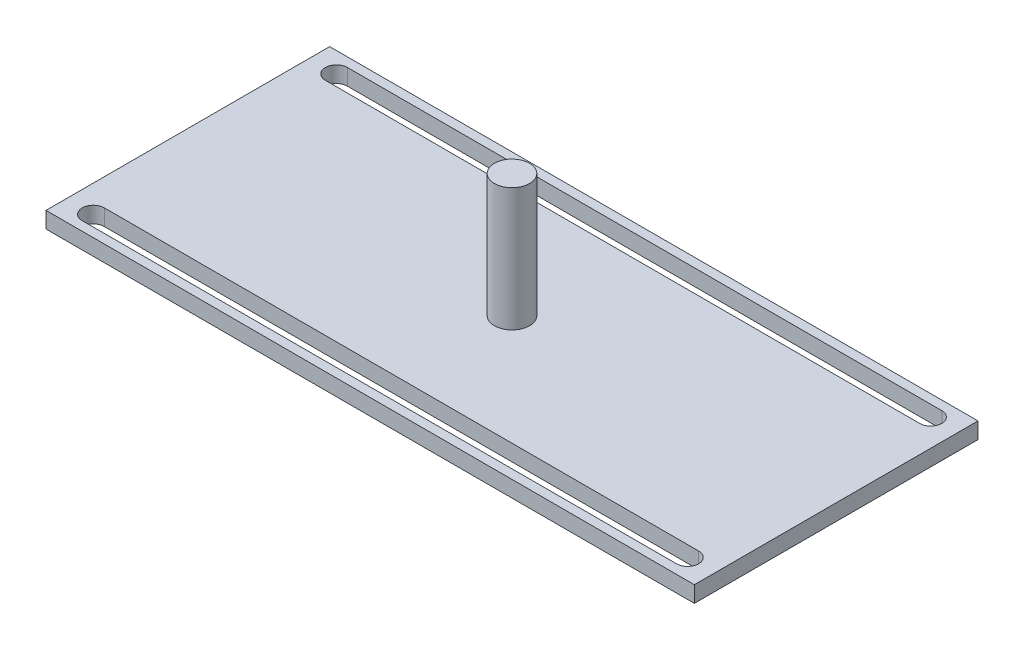
SolidWorks part; units mm, degrees
ref_plane "前视基准面" through (0, 0, 0) normal (0, 0, 1) x (1, 0, 0)
ref_plane "上视基准面" through (0, 0, 0) normal (0, 1, 0) x (1, 0, 0)
ref_plane "右视基准面" through (0, 0, 0) normal (1, 0, 0) x (0, 0, -1)
other "Configuration Table"
sketch "草图2" plane through (0, 0, 0) normal (0, 1, 0) x (1, 0, 0)
  line L1 (-205.4764, 85.5388) -> (34.5236, 85.5388)
  line L2 (-205.4764, 85.5388) -> (-205.4764, -19.4612)
  line L3 (-205.4764, -19.4612) -> (34.5236, -19.4612)
  line L4 (34.5236, 85.5388) -> (34.5236, -19.4612)
  dimension "D1" = 105
  dimension "D2" = 240
extrude "凸台-拉伸1" add sketch "草图2" along normal blind 6
sketch "草图17" plane through (0, 6, 0) normal (0, 1, 0) x (1, 0, 0)
  line L0 (-85.4764, 85.5388) -> (-85.4764, -19.4612) construction
  line L1 (34.5236, 85.5388) -> (-205.4764, 85.5388) construction
  line L2 (-205.4764, -19.4612) -> (34.5236, -19.4612) construction
ref_plane "基准面1" through (-85.4764, 0, 0) normal (1, 0, 0) x (0, 0, -1)
sketch "草图18" plane through (0, 6, 0) normal (0, 1, 0) x (1, 0, 0)
  line L0 (-205.4764, 33.0388) -> (34.5236, 33.0388) construction
  line L1 (-205.4764, 85.5388) -> (-205.4764, -19.4612) construction
  line L2 (34.5236, -19.4612) -> (34.5236, 85.5388) construction
  line L3 (-205.4764, 33.0388) -> (34.5236, 33.0388) construction
  circle A0 centre (-85.4764, 33.0388) radius 6.5
  dimension "D1" = 13
ref_plane "基准面2" through (0, 0, -33.0388) normal (0, 0, 1) x (1, 0, 0)
sketch "草图22" plane through (0, 0, 0) normal (0, 1, 0) x (1, 0, 0)
  line L0 (34.5236, 85.5388) -> (-205.4764, 85.5388) construction
  line L1 (-205.4764, 85.5388) -> (-205.4764, -19.4612) construction
  circle A0 centre (-195.4764, 78.0388) radius 4.1
  dimension "D1" = 8.2
  dimension "D2" = 7.5
  dimension "D3" = 10
extrude "切除-拉伸3" cut sketch "草图22" along normal through all
mirror "镜向18" about plane through (0, 0, -33.0388) normal (0, 0, 1) of "切除-拉伸3"
pattern_linear "阵列(线性)2" count 5 spacing 55 along (1, 0, 0) of "切除-拉伸3"
pattern_linear "阵列(线性)3" count 5 spacing 55 along (1, 0, 0) of "镜向18"
extrude "凸台-拉伸5" add sketch "草图18" along normal blind 45.6
sketch "草图25" plane through (0, 0, 0) normal (0, 1, 0) x (1, 0, 0)
  line L3 (-195.4764, 73.9388) -> (-195.4764, 82.1388)
  line L4 (-195.4764, 82.1388) -> (-85.4764, 82.1388)
  line L5 (-85.4764, 82.1388) -> (-85.4764, 73.9388)
  line L6 (-85.4764, 73.9388) -> (-195.4764, 73.9388)
  circle A0 centre (-195.4764, 78.0388) radius 4.1 construction
  circle A3 centre (-85.4764, 78.0388) radius 4.1 construction
extrude "切除-拉伸4" cut sketch "草图25" along normal through all
mirror "镜向25" about plane through (0, 0, -33.0388) normal (0, 0, 1) of "切除-拉伸4"
mirror "镜向26" about plane through (-85.4764, 0, 0) normal (1, 0, 0) of "切除-拉伸4"
mirror "镜向27" about plane through (-85.4764, 0, 0) normal (1, 0, 0) of "镜向25"
